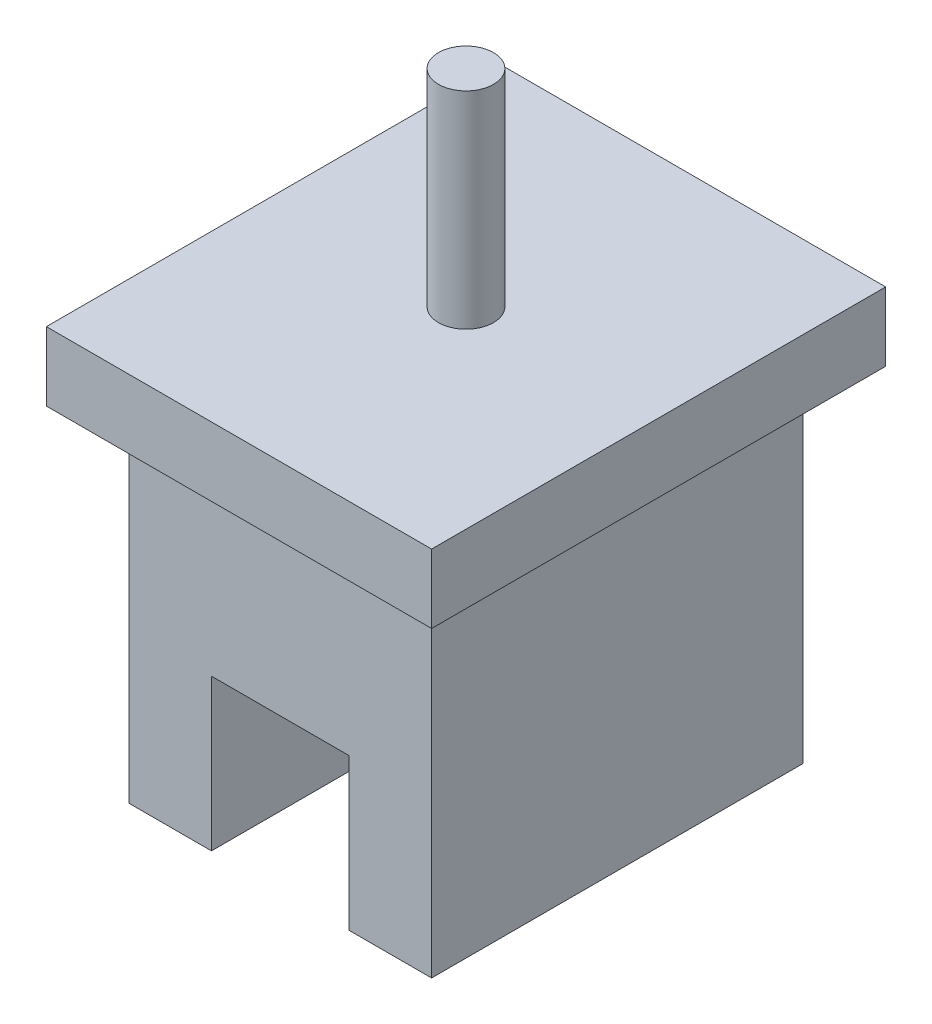
SolidWorks part; units mm, degrees
material "ABS"
ref_plane "Front Plane" through (0, 0, 0) normal (0, 0, 1) x (1, 0, 0)
ref_plane "Top Plane" through (0, 0, 0) normal (0, 1, 0) x (1, 0, 0)
ref_plane "Right Plane" through (0, 0, 0) normal (1, 0, 0) x (0, 0, -1)
other "Configuration Table"
sketch "Sketch1" plane through (0, 0, 0) normal (0, 1, 0) x (1, 0, 0)
  line L1 (-14, -16.5) -> (14, -16.5)
  line L2 (-14, -16.5) -> (-14, 16.5)
  line L3 (-14, 16.5) -> (14, 16.5)
  line L4 (14, -16.5) -> (14, 16.5)
  line L5 (-14, -16.5) -> (14, 16.5) construction
  line L6 (-14, 16.5) -> (14, -16.5) construction
  point P6 (0, 0)
  dimension "D1" = 28
  dimension "D2" = 33
extrude "Flange" add sketch "Sketch1" along normal blind 5
sketch "Sketch2" plane through (0, 0, 0) normal (0, 1, 0) x (1, 0, 0)
  line L0 (-11, -13.5) -> (11, -13.5)
  line L1 (11, -13.5) -> (11, 13.5)
  line L2 (11, 13.5) -> (-11, 13.5)
  line L3 (-11, 13.5) -> (-11, -13.5)
extrude "Neck" add sketch "Sketch2" along normal blind 14 from offset 14
sketch "Sketch3" plane through (0, 0, 0) normal (0, 1, 0) x (1, 0, 0)
  line L0 (-11, -13.5) -> (11, -13.5)
  line L1 (11, -13.5) -> (11, 13.5)
  line L2 (11, 13.5) -> (-11, 13.5)
  line L3 (-11, 13.5) -> (-11, -13.5)
extrude "Prongs" add sketch "Sketch3" along normal blind 11 from offset 25
sketch "Sketch4" plane through (0, 0, 0) normal (0, 0, 1) x (1, 0, 0)
  line L1 (-5, -26) -> (5, -26)
  line L2 (-5, -26) -> (-5, -14)
  line L3 (-5, -14) -> (5, -14)
  line L4 (5, -26) -> (5, -14)
  line L5 (-5, -26) -> (5, -14) construction
  line L6 (-5, -14) -> (5, -26) construction
  point P5 (0, -20)
  dimension "D1" = 10
  dimension "D2" = 12
extrude "Sensing_Slot" cut sketch "Sketch4" along normal through all and the other way through all
sketch "Sketch5" plane through (0, 0, 0) normal (0, 1, 0) x (1, 0, 0)
  circle A0 centre (0, 0) radius 2
  dimension "D1" = 4
extrude "Cable_Stub" add sketch "Sketch5" along normal blind 15 from offset 5
equation "\"Jar_OD\"= 90  'ASSUMED - Part G fallback - jar outer diameter"
equation "\"Jar_H\"= 120  'ASSUMED - Part G fallback - jar height"
equation "\"Pump_L\"= 45  'ASSUMED - Part G fallback"
equation "\"Pump_W\"= 24  'ASSUMED - Part G fallback"
equation "\"Pump_H\"= 33  'ASSUMED - Part G fallback"
equation "\"Pump_Outlet_OD\"= 7.5  'ASSUMED - Part G fallback"
equation "\"Tube_OD\"= 8  'ASSUMED - Part G fallback"
equation "\"Tube_ID\"= 6  'ASSUMED - Part G fallback"
equation "\"TDS_Body_Dia\"= 12  'ASSUMED - Part G fallback"
equation "\"TDS_Wet_Len\"= 45  'ASSUMED - Part G fallback - length in water"
equation "\"DS_Tube_Dia\"= 6  'ASSUMED - Part G fallback"
equation "\"DS_Tube_Len\"= 50  'ASSUMED - Part G fallback"
equation "\"ORP_Body_Dia\"= 12  'ASSUMED - Part G fallback"
equation "\"ORP_Body_Len\"= 150  'ASSUMED - Part G fallback"
equation "\"ORP_Cap_Dia\"= 16  'ASSUMED - Part G fallback"
equation "\"Turb_W\"= 33  'ASSUMED - Part G fallback - head width"
equation "\"Turb_D\"= 28  'ASSUMED - Part G fallback - head depth"
equation "\"Turb_H\"= 30  'ASSUMED - Part G fallback - head height"
equation "\"Turb_Slot_W\"= 10  'ASSUMED - Part G fallback - slot width"
equation "\"Flow_L\"= 62  'ASSUMED - Part G fallback YF-S201"
equation "\"Flow_W\"= 36  'ASSUMED - Part G fallback"
equation "\"Flow_H\"= 35  'ASSUMED - Part G fallback"
equation "\"Thread_G12_OD\"= 20.955  'ASSUMED - Part G fallback thread G1/2 (major diameter)"
equation "\"Valve_L\"= 75  'ASSUMED - Part G fallback"
equation "\"Valve_W\"= 45  'ASSUMED - Part G fallback"
equation "\"Valve_H\"= 60  'ASSUMED - Part G fallback"
equation "\"Tee_L\"= 40  'ASSUMED - Part G fallback - overall length"
equation "\"Tee_Branch_L\"= 25  'ASSUMED - Part G fallback"
equation "\"Tee_OD\"= 12  'ASSUMED - Part G fallback"
equation "\"Cuv_W\"= 12.5  'ASSUMED - old R3 cuvette (station suppressed in SS4)"
equation "\"Cuv_D\"= 12.5  'ASSUMED - old R3 cuvette (station suppressed in SS4)"
equation "\"Cuv_H\"= 45  'ASSUMED - old R3 cuvette (station suppressed in SS4)"
equation "\"LED_Board_L\"= 20  'ASSUMED - Part G fallback"
equation "\"LED_Board_W\"= 20  'ASSUMED - Part G fallback - LED at centre"
equation "\"GUVA_L\"= 20  'ASSUMED - Part G fallback"
equation "\"GUVA_W\"= 12  'ASSUMED - Part G fallback - sensor at centre"
equation "\"Reed_L\"= 27  'ASSUMED - Part G fallback MC-38 half"
equation "\"Reed_W\"= 14  'ASSUMED - Part G fallback"
equation "\"Reed_H\"= 8  'ASSUMED - Part G fallback"
equation "\"ESP_L\"= 51  'ASSUMED - Part G fallback"
equation "\"ESP_W\"= 28  'ASSUMED - Part G fallback"
equation "\"TFT_L\"= 58  'ASSUMED - Part G fallback - board"
equation "\"TFT_W\"= 35  'ASSUMED - Part G fallback - board"
equation "\"TFT_Win_L\"= 35  'ASSUMED - Part G fallback - visible window"
equation "\"TFT_Win_W\"= 28  'ASSUMED - Part G fallback - visible window"
equation "\"Relay_L\"= 50  'ASSUMED - Part G fallback"
equation "\"Relay_W\"= 26  'ASSUMED - Part G fallback"
equation "\"Relay_H\"= 19  'ASSUMED - Part G fallback"
equation "\"Mosfet_L\"= 34  'ASSUMED - Part G fallback"
equation "\"Mosfet_W\"= 17  'ASSUMED - Part G fallback"
equation "\"Mosfet_H\"= 12  'ASSUMED - Part G fallback"
equation "\"TDS_Board_L\"= 42  'ASSUMED - Part G fallback"
equation "\"TDS_Board_W\"= 32  'ASSUMED - Part G fallback"
equation "\"Turb_Board_L\"= 38  'ASSUMED - Part G fallback"
equation "\"Turb_Board_W\"= 28  'ASSUMED - Part G fallback"
equation "\"BNC_Thread_Dia\"= 9.5  'ASSUMED - Part G fallback"
equation "\"Plate_L\"= 420  'ASSUMED - Part G fallback"
equation "\"Plate_W\"= 297  'ASSUMED - Part G fallback"
equation "\"Plate_T\"= 6  'ASSUMED - Part G fallback"
equation "\"Probe_Clr\"= 0.3  'DESIGN VALUE - Part C rule 3 - printed probe hole = diameter + 0.3"
equation "\"Cuv_Clr\"= 0.2  'DESIGN VALUE - Part C rule 3 - cuvette pocket = size + 0.2"
equation "\"Label_H\"= 0.6  'DESIGN VALUE - Part D - raised label height"
equation "\"D1@Sketch1\" = \"Turb_D\""
equation "\"D2@Sketch1\" = \"Turb_W\""
equation "\"D1@Sketch4\" = \"Turb_Slot_W\""
equation "\"Booster_L\"= 150  'ASSUMED - Part G fallback - booster pump"
equation "\"Booster_W\"= 95  'ASSUMED - Part G fallback"
equation "\"Booster_H\"= 100  'ASSUMED - Part G fallback"
equation "\"PTube_OD\"= 6.35  'ASSUMED - Part G fallback - product tube 1/4 inch"
equation "\"Qz_Out\"= 12  'ASSUMED - Part G fallback - quartz channel outside square"
equation "\"Qz_Path\"= 10  'ASSUMED - Part G fallback - quartz channel inside light path"
equation "\"Qz_L\"= 40  'ASSUMED - Part G fallback - quartz channel length"
equation "\"LED860_Dia\"= 5  'ASSUMED - Part G fallback - 860 nm LED"
equation "\"BPW_L\"= 5.4  'ASSUMED - Part G fallback - BPW34"
equation "\"BPW_W\"= 4.3  'ASSUMED - Part G fallback - BPW34"
equation "\"Cart_Dia\"= 50  'ASSUMED - Part G fallback - sediment and pre-carbon cartridges"
equation "\"Cart_L\"= 255  'ASSUMED - Part G fallback"
equation "\"UF_Dia\"= 50  'ASSUMED - Part G fallback - UF cartridge"
equation "\"UF_L\"= 260  'ASSUMED - Part G fallback"
equation "\"RO_Dia\"= 62  'ASSUMED - Part G fallback - RO membrane housing"
equation "\"RO_L\"= 300  'ASSUMED - Part G fallback"
equation "\"UVC_Dia\"= 40  'ASSUMED - Part G fallback - UV-C chamber"
equation "\"UVC_L\"= 300  'ASSUMED - Part G fallback"
equation "\"Tank_W\"= 260  'ASSUMED - Part G fallback - storage tank"
equation "\"Tank_D\"= 160  'ASSUMED - Part G fallback"
equation "\"Tank_H\"= 300  'ASSUMED - Part G fallback"
equation "\"Cab_W\"= 400  'ASSUMED - Part G fallback - purifier cabinet"
equation "\"Cab_D\"= 270  'ASSUMED - Part G fallback"
equation "\"Cab_H\"= 560  'ASSUMED - Part G fallback"
equation "\"ORP_Board_L\"= 40  'ASSUMED - Part G fallback - ORP buffer board"
equation "\"ORP_Board_W\"= 30  'ASSUMED - Part G fallback"
equation "\"Opt_Board_L\"= 50  'ASSUMED - Part G fallback - optical front-end board"
equation "\"Opt_Board_W\"= 40  'ASSUMED - Part G fallback"
equation "\"Buck_L\"= 43  'ASSUMED - Part G fallback - 12 V to 5 V buck module"
equation "\"Buck_W\"= 21  'ASSUMED - Part G fallback"
equation "\"Buck_H\"= 14  'ASSUMED - Part G fallback"
equation "\"BB_L\"= 165  'ASSUMED - Part G fallback - breadboard (As_Built_R3 only)"
equation "\"BB_W\"= 55  'ASSUMED - Part G fallback"
equation "\"BB_H\"= 10  'ASSUMED - Part G fallback"
